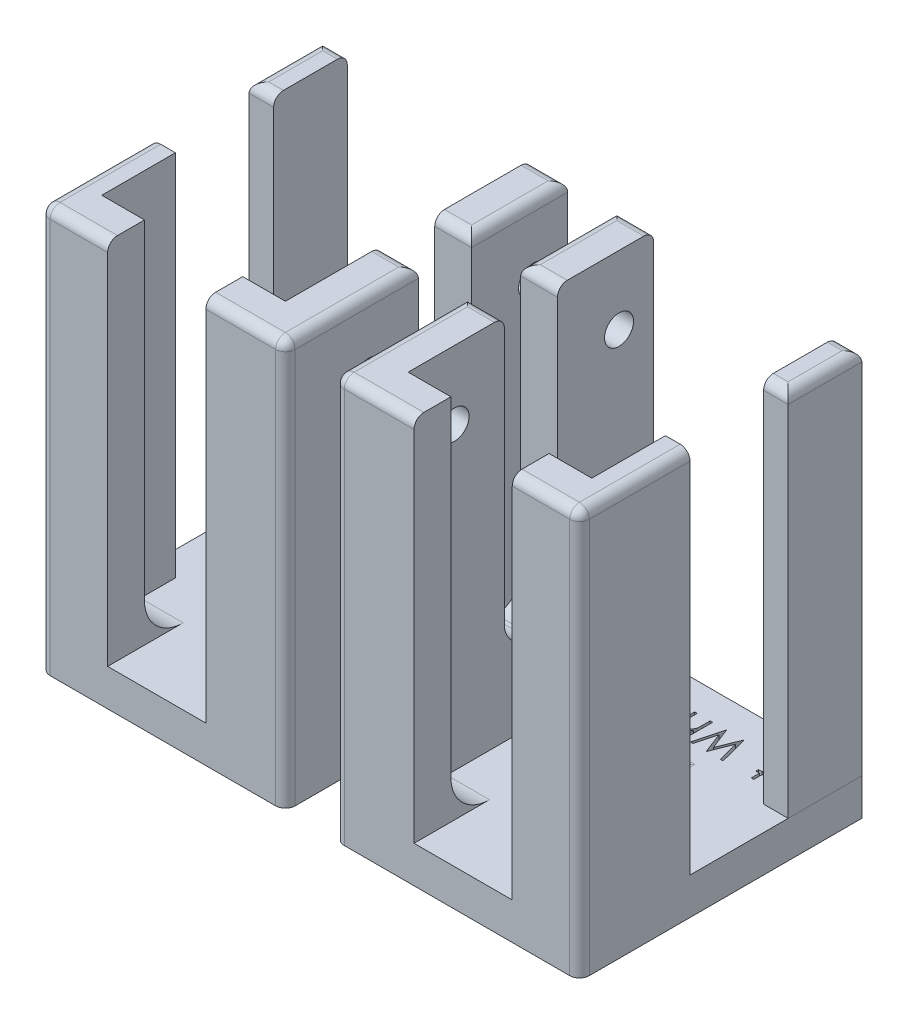
SolidWorks part; units mm, degrees
ref_plane "Front Plane" through (0, 0, 0) normal (0, 0, 1) x (1, 0, 0)
ref_plane "Top Plane" through (0, 0, 0) normal (0, 1, 0) x (1, 0, 0)
ref_plane "Right Plane" through (0, 0, 0) normal (1, 0, 0) x (0, 0, -1)
sketch "Sketch2" plane through (0, 0, 0) normal (0, 1, 0) x (1, 0, 0)
  line L5 (12.04, -12.7) -> (9.5, -12.7)
  line L10 (-13.31, -12.7) -> (-13.31, 16.51)
  line L15 (-13.31, 16.51) -> (12.04, 16.51)
  line L16 (12.04, 16.51) -> (12.04, 5.08)
  line L17 (12.04, -12.7) -> (12.04, -5.08)
  line L18 (12.04, 5.08) -> (9.5, 5.08)
  line L19 (9.5, 5.08) -> (9.5, 12.7)
  line L20 (9.5, 12.7) -> (-9.5, 12.7)
  line L21 (-9.5, 12.7) -> (-9.5, -12.7)
  line L22 (12.04, -5.08) -> (9.5, -5.08)
  line L23 (-9.5, -12.7) -> (-13.31, -12.7)
  line L24 (9.5, -12.7) -> (9.5, -5.08)
  point P6 (0, 12.7)
  point P12 (-9.5, 0)
  dimension "D1" = 25.4
  dimension "D2" = 19
  dimension "D3" = 3.81
  dimension "D4" = 3.81
  dimension "D5" = 5.08
  dimension "D6" = 2.54
  dimension "D7" = 5.08
extrude "Boss-Extrude2" add sketch "Sketch2" along normal blind 38.1
sketch "Sketch1" plane through (0, 0, 0) normal (0, 1, 0) x (1, 0, 0)
  line L1 (-13.31, -12.7) -> (12.04, -12.7)
  line L2 (-13.31, -12.7) -> (-13.31, 16.51)
  line L3 (-13.31, 16.51) -> (12.04, 16.51)
  line L4 (12.04, -12.7) -> (12.04, 16.51)
  point P0 (0, 0)
extrude "Boss-Extrude3" add sketch "Sketch1" against normal blind 3.81
sketch "Sketch3" plane through (0, 0, 0) normal (0, 1, 0) x (1, 0, 0)
  line L1 (-1.88, -3.81) -> (1.12, -3.81)
  line L2 (-1.88, -3.81) -> (-1.88, 3.81)
  line L3 (-1.88, 3.81) -> (1.12, 3.81)
  line L4 (1.12, -3.81) -> (1.12, 3.81)
  line L5 (-9.5, -12.7) -> (-9.5, 12.7) construction
  point P6 (-1.88, 0)
  dimension "D1" = 7.62
  dimension "D2" = 3
  dimension "D3" = 7.62
extrude "Cut-Extrude1" cut sketch "Sketch3" against normal through all
sketch "Sketch4" plane through (-9.5, 0, 0) normal (1, 0, 0) x (0, 0, -1)
  line L0 (-12.7, 38.1) -> (12.7, 38.1) construction
  line L1 (-2.75, 38.1) -> (2.75, 38.1)
  line L2 (-2.75, 38.1) -> (-2.75, 8)
  line L3 (-2.75, 8) -> (2.75, 8)
  line L4 (2.75, 38.1) -> (2.75, 8)
  line L5 (-12.7, 0) -> (12.7, 0) construction
  line L6 (-12.7, 38.1) -> (12.7, 38.1) construction
  point P10 (0, 38.1)
  point P11 (0, 38.1)
  dimension "D1" = 8
  dimension "D2" = 5.5
extrude "Cut-Extrude2" cut sketch "Sketch4" against normal through all
sketch "Sketch9" plane through (0, 0, -12.7) normal (0, 0, 1) x (1, 0, 0)
  line L0 (-9.5, 38.1) -> (9.5, 38.1) construction
  line L1 (-5.08, 38.1) -> (5.08, 38.1)
  line L2 (-5.08, 38.1) -> (-5.08, 0)
  line L3 (-5.08, 0) -> (5.08, 0)
  line L4 (5.08, 38.1) -> (5.08, 0)
  line L5 (-13.31, 8) -> (-9.5, 8) construction
  line L6 (-9.5, 0) -> (9.5, 0) construction
  point P8 (0, 38.1)
  point P9 (0, 38.1)
  dimension "D1" = 10.16
extrude "Cut-Extrude7" cut sketch "Sketch9" against normal up to next (3.81 mm away)
sketch "Sketch5" plane through (-9.5, 0, 0) normal (1, 0, 0) x (0, 0, -1)
  line L0 (12.7, 38.1) -> (12.7, 0) construction
  line L1 (-12.7, 0) -> (12.7, 0) construction
  circle A0 centre (-9.118, 31) radius 1.5
  circle A1 centre (7.9, 31) radius 1.5
  dimension "D3" = 3
  dimension "D1" = 4.8
  dimension "D2" = 17.018
  dimension "D4" = 31
extrude "Cut-Extrude3" cut sketch "Sketch5" against normal through all
sketch "Sketch6" plane through (0, 0, 12.7) normal (0, 0, 1) x (1, 0, 0)
  line L1 (-9.5, 38.1) -> (-9.5, 0) construction
  line L4 (-13.31, 38.1) -> (-13.31, -3.81) construction
  line L5 (12.04, -3.81) -> (12.04, 0) construction
  line L7 (-13.31, 38.1) -> (-9.5, 38.1) construction
  circle A0 centre (-11.405, 19.05) radius 1.45
  circle A1 centre (-3.81, -1.905) radius 1.45
  point P12 (-9.5, 19.05)
  point P18 (12.04, -1.905)
  point P20 (-11.405, 38.1)
  dimension "D1" = 2.9
  dimension "D2" = 9.5
extrude "Cut-Extrude4" cut sketch "Sketch6" against normal offset from surface (22.054 mm away) 6.604 up to face at (-11.405, 23.05, -2.75) offset beyond the face yes
fillet "Fillet1" radius 4 2 edges at (7.29, 0, -12.7) (-7.29, 0, -12.7)
mirror "Mirror1" about plane through (0, 0, 0) normal (0, 0, 1) of bodies 106 120
delete or keep bodies "Body-Delete/Keep 1" type keep bodies bodies 116 121
fillet "Fillet4" radius 2.54 2 edges at (-11.405, 8, -2.75) (-11.405, 8, 2.75)
fillet "Fillet2" radius 1.016 10 edges at (-13.31, 17.145, 16.51) (12.04, 17.145, 16.51) (12.04, 38.1, 10.795) (8.56, 38.1, 16.51) (-13.31, 38.1, 9.63) (-11.405, 38.1, -12.7) (-13.31, 38.1, -7.725) (-11.405, 38.1, -2.75) (-11.405, 38.1, 2.75) (-9.195, 38.1, 16.51)
fillet "Fillet3" radius 1.27 4 edges at (-0.38, 0, -3.81) (-1.88, 0, 0) (-0.38, 0, 3.81) (1.12, 0, 0)
fillet "Fillet5" radius 1.016 3 edges at (10.77, 38.1, -5.08) (10.77, 38.1, -12.7) (12.04, 38.1, -8.89)
ref_plane "Plane1" through (-15.85, 0, 0) normal (-1, 0, 0) x (0, 0, 1)
mirror "Mirror3" about plane through (-15.85, 0, 0) normal (-1, 0, 0) of bodies 116 121 117
sketch "Sketch7" plane through (0, 0, 0) normal (0, 1, 0) x (1, 0, 0)
  line L0 (9.196, 9.7741) -> (-9.1456, 9.7741) construction
  text T0 "Lt. Wheel" font "Century Gothic" height in points 11
  point P3 (9.196, 9.7317)
  point P4 (-9.1456, 9.7741)
extrude "Cut-Extrude5" cut sketch "Sketch7" against normal blind 1.27
sketch "Sketch8" plane through (0, 0, 0) normal (0, 1, 0) x (1, 0, 0)
  line L0 (-41.0941, 9.8054) -> (-20.7741, 9.8054) construction
  text T0 "Rt. Wheel" font "Century Gothic" height in points 11
  point P3 (-23.622, 9.957)
  point P4 (-40.7897, 10.1379)
  point P5 (-41.0941, 9.8054)
  dimension "D1" = 20.32
extrude "Cut-Extrude6" cut sketch "Sketch8" against normal blind 1.27
equation "\".30.83in\"=0.83"
